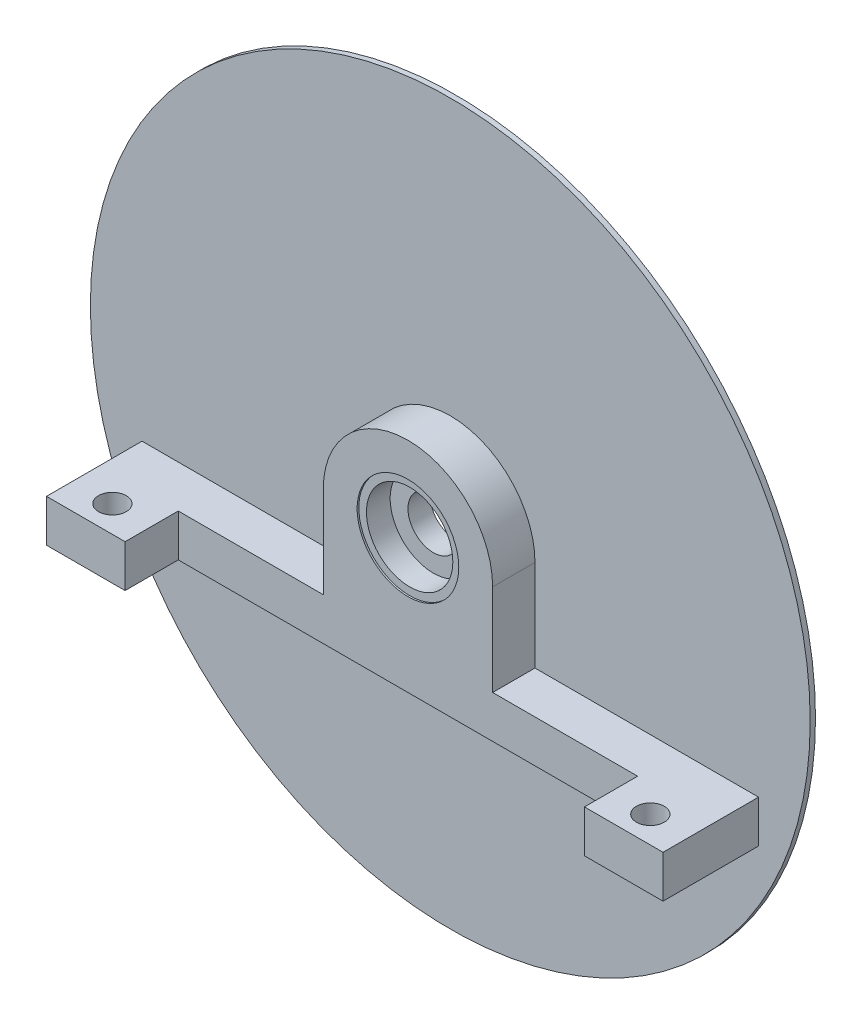
SolidWorks part; units mm, degrees
ref_plane "Front Plane" through (0, 0, 0) normal (0, 0, 1) x (1, 0, 0)
ref_plane "Top Plane" through (0, 0, 0) normal (0, 1, 0) x (1, 0, 0)
ref_plane "Right Plane" through (0, 0, 0) normal (1, 0, 0) x (0, 0, -1)
sketch "Sketch1" plane through (0, 0, 0) normal (0, 0, 1) x (1, 0, 0)
  line L0 (-12.7, 0) -> (-12.7, -13.716)
  line L1 (-12.7, -13.716) -> (-46.228, -13.716)
  line L2 (-46.228, -13.716) -> (-46.228, -20.066)
  line L3 (0, 0) -> (0, 22605.9957) construction
  line L4 (-46.228, -20.066) -> (46.228, -20.066)
  line L5 (46.228, -13.716) -> (46.228, -20.066)
  line L6 (12.7, -13.716) -> (46.228, -13.716)
  line L7 (12.7, 0) -> (12.7, -13.716)
  line L8 (-41.1226, -9.2487) -> (-41.1226, 49990.7513) construction
  line L9 (-36.8554, -18.7297) -> (-36.8554, 49981.2703) construction
  line L10 (-38.989, -13.9892) -> (-38.989, 49986.0108) construction
  line L12 (-41.1226, -13.716) -> (-36.8554, -13.716) construction
  line L13 (-41.1226, -13.716) -> (-41.1226, -20.066) construction
  line L14 (-41.1226, -20.066) -> (-36.8554, -20.066) construction
  line L15 (-36.8554, -13.716) -> (-36.8554, -20.066) construction
  line L16 (-41.1226, -13.716) -> (-36.8554, -20.066) construction
  line L17 (-41.1226, -20.066) -> (-36.8554, -13.716) construction
  line L18 (-42.418, -9.8692) -> (-35.56, -9.8692) construction
  line L19 (-42.418, -9.8692) -> (-42.418, -13.716) construction
  line L20 (-42.418, -13.716) -> (-35.56, -13.716) construction
  line L21 (-35.56, -9.8692) -> (-35.56, -13.716) construction
  line L22 (-42.418, -9.8692) -> (-35.56, -13.716) construction
  line L23 (-42.418, -13.716) -> (-35.56, -9.8692) construction
  circle A0 centre (0, 0) radius 3.81
  arc A1 (12.7, 0) -> (-12.7, 0) centre (0, 0) ccw
  point P6 (0, -20.066)
  point P20 (-38.989, -16.891)
  point P26 (-42.418, -11.7926)
  point P27 (-38.989, -11.7926)
  dimension "D1" = 7.62
  dimension "D2" = 12.7
  dimension "D3" = 6.35
  dimension "D4" = 20.066
  dimension "D5" = 6.858
  dimension "D6" = 4.2672
  dimension "D7" = 22.86
  dimension "D8" = 3.81
extrude "Boss-Extrude1" add sketch "Sketch1" along normal mid plane 6.35
sketch "Sketch2" plane through (0, 0, 3.175) normal (0, 0, 1) x (1, 0, 0)
  circle A0 centre (0, 0) radius 6.477
  dimension "D1" = 12.954
extrude "Cut-Extrude1" cut sketch "Sketch2" against normal blind 3.81
sketch "Sketch3" plane through (0, 0, 3.175) normal (0, 0, 1) x (1, 0, 0)
  circle A0 centre (0, 0) radius 7.62
  dimension "D1" = 15.24
extrude "Cut-Extrude2" cut sketch "Sketch3" against normal blind 0.254
sketch "Sketch6" plane through (0, 0, 3.175) normal (0, 0, 1) x (1, 0, 0)
  line L0 (-46.228, -20.066) -> (46.228, -20.066) construction
  line L1 (-46.228, -13.716) -> (-34.4424, -13.716)
  line L2 (-46.228, -13.716) -> (-46.228, -20.066)
  line L3 (-46.228, -20.066) -> (-34.4424, -20.066)
  line L4 (-34.4424, -13.716) -> (-34.4424, -20.066)
  dimension "D1" = 11.7856
extrude "Boss-Extrude2" add sketch "Sketch6" along normal blind 7.9756
sketch "Sketch7" plane through (0, -13.716, 0) normal (0, 1, 0) x (1, 0, 0)
  line L0 (-40.3352, -14.9606) -> (-40.3352, 49985.0394) construction
  line L1 (-34.4424, -11.1506) -> (-46.228, -11.1506) construction
  line L2 (-28.0924, -7.1628) -> (-50028.0924, -7.1628) construction
  line L3 (-34.4424, -11.1506) -> (-34.4424, -3.175) construction
  circle A0 centre (-40.3352, -7.1628) radius 2.0828
  point P4 (-40.3352, -11.1506)
  point P9 (-34.4424, -7.1628)
  dimension "D1" = 4.1656
extrude "Cut-Extrude4" cut sketch "Sketch7" against normal through all
mirror "Mirror2" about plane through (0, 0, 0) normal (1, 0, 0) of "Cut-Extrude4", "Boss-Extrude2"
sketch "Sketch8" plane through (0, 0, -3.175) normal (0, 0, -1) x (-1, 0, 0)
  circle A0 centre (0, 0) radius 53.975
  circle A1 centre (0, 0) radius 3.81 construction
  circle A2 centre (0, 0) radius 3.81
  dimension "D1" = 107.95
extrude "Boss-Extrude4" add sketch "Sketch8" along normal blind 0.7937
